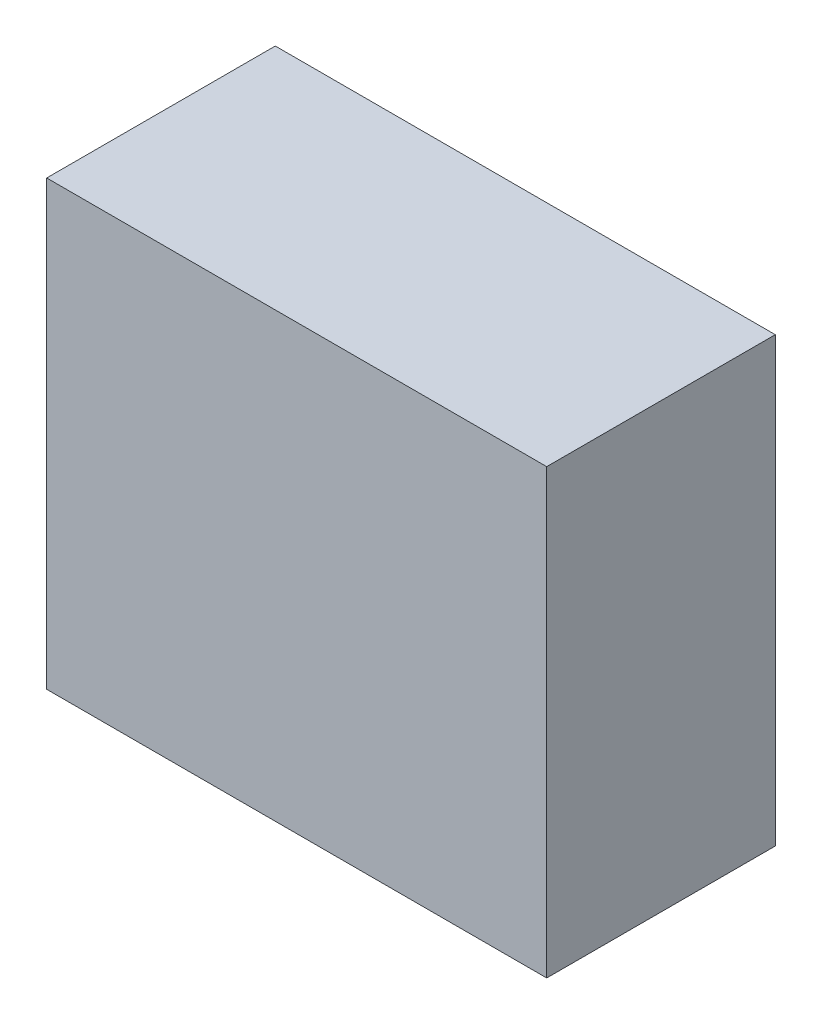
SolidWorks part; units mm, degrees
ref_plane "Front Plane" through (0, 0, 0) normal (0, 0, 1) x (1, 0, 0)
ref_plane "Top Plane" through (0, 0, 0) normal (0, 1, 0) x (1, 0, 0)
ref_plane "Right Plane" through (0, 0, 0) normal (1, 0, 0) x (0, 0, -1)
sketch "Sketch1" plane through (0, 0, 0) normal (0, 0, 1) x (1, 0, 0)
  line L1 (-48.2199, 21.7801) -> (21.7801, 21.7801)
  line L2 (-48.2199, 21.7801) -> (-48.2199, -40.2199)
  line L3 (-48.2199, -40.2199) -> (21.7801, -40.2199)
  line L4 (21.7801, 21.7801) -> (21.7801, -40.2199)
  dimension "D1" = 70
  dimension "D2" = 62
extrude "Boss-Extrude1" add sketch "Sketch1" along normal blind 32
